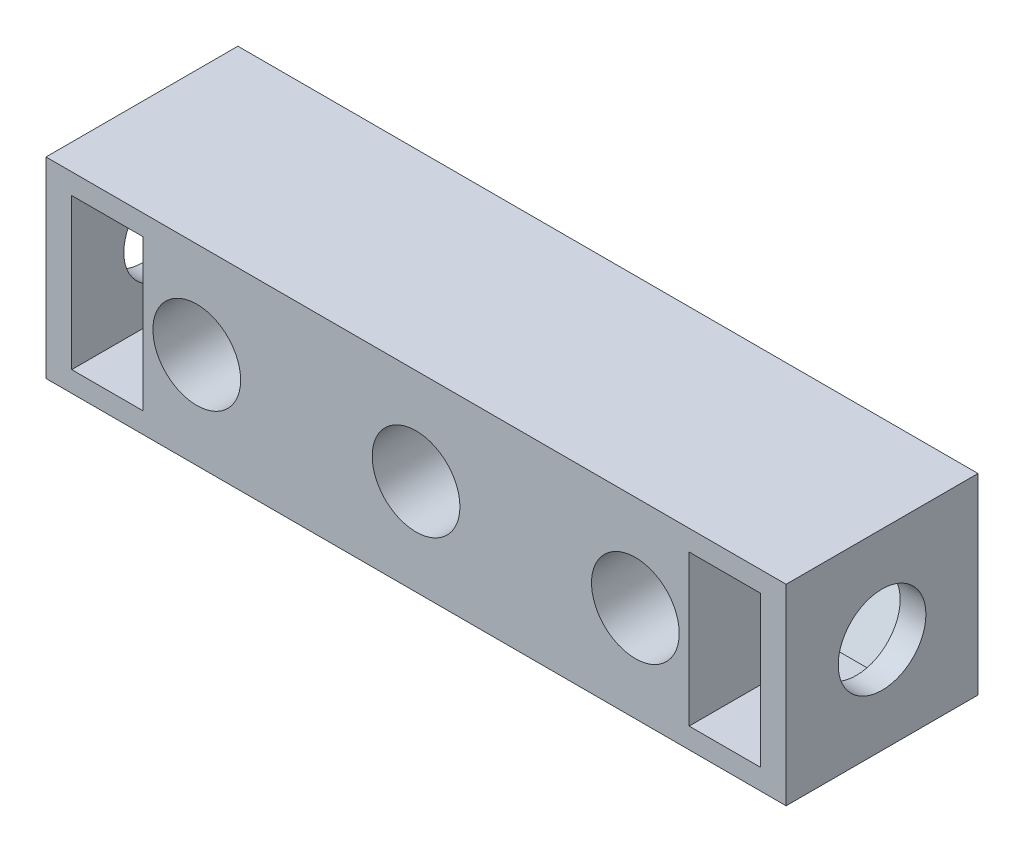
SolidWorks part; units mm, degrees
ref_plane "Front Plane" through (0, 0, 0) normal (0, 0, 1) x (1, 0, 0)
ref_plane "Top Plane" through (0, 0, 0) normal (0, 1, 0) x (1, 0, 0)
ref_plane "Right Plane" through (0, 0, 0) normal (1, 0, 0) x (0, 0, -1)
sketch "Sketch1" plane through (0, 0, 0) normal (0, 0, 1) x (1, 0, 0)
  line L1 (-28.5, 39.75) -> (-1.5, 39.75)
  line L2 (-28.5, 39.75) -> (-28.5, 32.75)
  line L3 (-28.5, 32.75) -> (-1.5, 32.75)
  line L4 (-1.5, 39.75) -> (-1.5, 32.75)
  dimension "D1" = 7
  dimension "D2" = 27
extrude "Boss-Extrude1" add sketch "Sketch1" along normal blind 7 contours L3 L4 L1 L2
hole_wizard "Side Shaft Holes (M3)" positions "Sketch3" profile "Sketch2" hole size "M3" standard "ANSI Metric"
sketch "Sketch3" plane through (-1.5, 0, 0) normal (1, 0, 0) x (0, 0, -1)
  line L0 (0, 32.75) -> (-7, 39.75) construction
  line L3 (-7, 32.75) -> (0, 32.75) construction
  line L4 (-7, 39.75) -> (-7, 32.75) construction
  line L5 (-7, 32.75) -> (0, 32.75) construction
  line L6 (-7, 39.75) -> (-7, 32.75) construction
  point P6 (-3.5, 36.25)
  point P26 (45.3129, 36.25)
sketch "Sketch2" plane through (-1.5, 36.25, 3.5) normal (0, 1, 0) x (0, 0, -1)
  line L0 (0, 0) -> (0, 4)
  line L1 (0, 4) -> (1.6, 3.0386)
  line L2 (1.6, 3.0386) -> (1.6, 0)
  line L5 (1.6, 0) -> (0, 0)
  line L10 (0, 4) -> (-1.6, 3.0386) construction
  line L11 (0, -6.35) -> (0, 107.95) construction
  dimension "Hole Dia." = 3.2
  dimension "Hole Depth" = 4
  dimension "Drill Angle" = 118
ref_plane "Plane2" through (-4.5386, 0, 0) normal (-1, 0, 0) x (0, 0, 1)
sketch "Sketch9" plane through (-4.5386, 0, 0) normal (-1, 0, 0) x (0, 0, 1)
  circle A0 centre (3.5, 36.25) radius 1.6 construction
  circle A1 centre (3.5, 36.25) radius 1.6
extrude "Boss-Extrude2" add sketch "Sketch9" along normal blind 3.4
ref_plane "Midplane" through (-15, 0, 0) normal (-1, 0, 0) x (0, 0, 1)
mirror "Shaft Hole Mirror" about plane through (-15, 0, 0) normal (-1, 0, 0) of "Boss-Extrude2", "Side Shaft Holes (M3)"
hole_wizard "M3 Clearance Hole1" positions "Sketch6" profile "Sketch7" hole size "M3" standard "ANSI Metric" end condition up to next
sketch "Sketch6" plane through (0, 0, 7) normal (0, 0, 1) x (1, 0, 0)
  line L0 (-5.5, 36.25) -> (-4.5386, 34.65) construction
  line L1 (-4.5386, 37.85) -> (-5.5, 36.25) construction
  line L2 (-25.4614, 34.65) -> (-24.5, 36.25) construction
  line L3 (-24.5, 36.25) -> (-25.4614, 37.85) construction
  line L4 (-5.5, 36.25) -> (-4.5386, 34.65) construction
  line L5 (-4.5386, 37.85) -> (-5.5, 36.25) construction
  line L6 (-25.4614, 34.65) -> (-24.5, 36.25) construction
  line L7 (-24.5, 36.25) -> (-25.4614, 37.85) construction
  line L8 (-24.5, 36.25) -> (-24.5, 44.3288) construction
  line L10 (-5.5, 37.5) -> (-5.5, 44.8277) construction
  line L13 (-24.5, 36.25) -> (-23, 36.25) construction
  line L14 (-23, 36.25) -> (-15, 36.25) construction
  line L15 (-15, 36.25) -> (-7, 36.25) construction
  line L16 (-7, 36.25) -> (-5.5, 36.25) construction
  line L18 (-24.5, 39.75) -> (-5.5, 39.75) construction
  line L19 (-28.5, 39.75) -> (-1.5, 39.75) construction
  point P27 (-15, 36.25)
  point P29 (-23, 36.25)
  point P31 (-7, 36.25)
  point P53 (-15, 39.75)
  dimension "D1" = 8
sketch "Sketch7" plane through (-7, 36.25, 7) normal (1, 0, 0) x (0, -1, 0)
  line L0 (0, 0) -> (0, 7)
  line L1 (0, 7) -> (1.6, 7)
  line L2 (1.6, 7) -> (1.6, 0)
  line L5 (1.6, 0) -> (0, 0)
  line L11 (0, -6.35) -> (0, 107.95) construction
  dimension "Thru Hole Dia." = 3.2
  dimension "Thru Hole Depth" = 7
ref_plane "Plane1" through (-4.5386, 0, 0) normal (-1, 0, 0) x (0, 0, 1)
sketch "Sketch8" plane through (-4.5386, 0, 0) normal (-1, 0, 0) x (0, 0, 1)
  line L0 (7, 32.75) -> (0, 32.75) construction
  line L1 (0.3246, 36.25) -> (1.9123, 33.5)
  line L2 (1.9123, 33.5) -> (5.0877, 33.5)
  line L3 (5.0877, 33.5) -> (6.6754, 36.25) construction
  line L4 (6.6754, 36.25) -> (5.0877, 39) construction
  line L5 (5.0877, 39) -> (1.9123, 39)
  line L6 (1.9123, 39) -> (0.3246, 36.25)
  line L7 (5.0877, 33.5) -> (7, 33.5)
  line L8 (7, 39.75) -> (7, 32.75) construction
  line L9 (7, 33.5) -> (7, 39)
  line L10 (7, 39) -> (5.0877, 39)
  circle A0 centre (3.5, 36.25) radius 1.6 construction
  circle A1 centre (3.5, 36.25) radius 1.6 construction
  circle A2 centre (3.5, 36.25) radius 2.75 construction
  dimension "D1" = 5.5
extrude "Cut-Extrude1" cut sketch "Sketch8" along normal blind 0.5 and the other way blind 2.1 contours L9 L10 L5 L6 L1 L2 L7
mirror "Mirror1" about plane through (-15, 0, 0) normal (-1, 0, 0) of "Cut-Extrude1"
